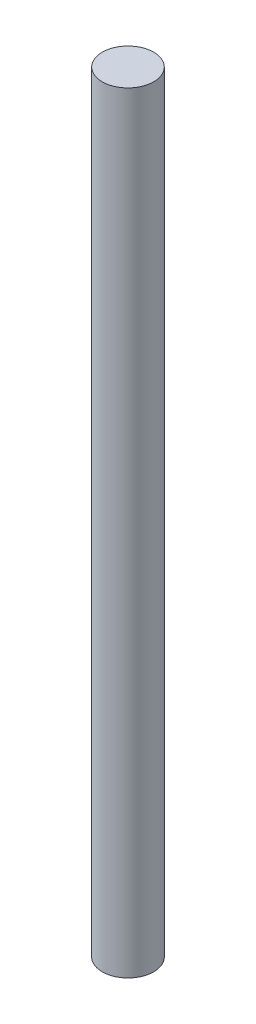
SolidWorks part; units mm, degrees
ref_plane "Front Plane" through (0, 0, 0) normal (0, 0, 1) x (1, 0, 0)
ref_plane "Top Plane" through (0, 0, 0) normal (0, 1, 0) x (1, 0, 0)
ref_plane "Right Plane" through (0, 0, 0) normal (1, 0, 0) x (0, 0, -1)
sketch "Sketch1" plane through (0, 0, 0) normal (0, 1, 0) x (1, 0, 0)
  circle A0 centre (0, 0) radius 10
  dimension "D1" = 20
extrude "Boss-Extrude1" add sketch "Sketch1" against normal blind 300
sketch "Sketch2" plane through (0, 0, 0) normal (0, 0, 1) x (1, 0, 0)
  circle A0 centre (0, -22.3791) radius 2
extrude "Cut-Extrude1" cut sketch "Sketch2" against normal blind 300
